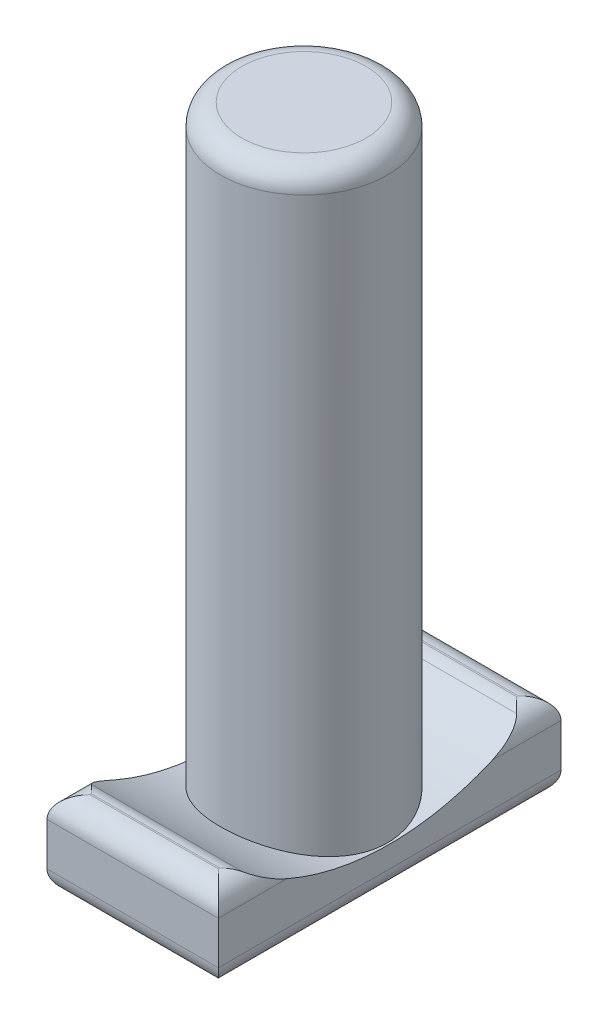
SolidWorks part; units mm, degrees
ref_plane "前视基准面" through (0, 0, 0) normal (0, 0, 1) x (1, 0, 0)
ref_plane "上视基准面" through (0, 0, 0) normal (0, 1, 0) x (1, 0, 0)
ref_plane "右视基准面" through (0, 0, 0) normal (1, 0, 0) x (0, 0, -1)
sketch "草图1" plane through (0, 0, 0) normal (0, 1, 0) x (1, 0, 0)
  line L1 (0, 0) -> (4, 0)
  line L2 (0, 0) -> (0, 8)
  line L3 (0, 8) -> (4, 8)
  line L4 (4, 0) -> (4, 8)
  circle A0 centre (2, 4) radius 1.95
  point P9 (4, 4.9563)
  dimension "D3" = 3.9
  dimension "D4" = 4
  dimension "D1" = 4
  dimension "D2" = 8
  dimension "D5" = 2
extrude "凸台-拉伸1" add sketch "草图1" along normal blind 2
sketch "草图2" plane through (0, 0, 0) normal (0, -1, 0) x (1, 0, 0)
  circle A0 centre (2, -4) radius 1.95
sketch "草图3" plane through (0, 0, 0) normal (-1, 0, 0) x (0, 0, 1)
  line L0 (-8, 2) -> (0, 2) construction
  line L1 (-8, 2) -> (-8, 0) construction
  circle A0 centre (-4, 7) radius 6
  dimension "D2" = 12
  dimension "D1" = 5
  dimension "D3" = 4
extrude "切除-拉伸1" cut sketch "草图3" against normal through all
extrude "凸台-拉伸3" add sketch "草图2" against normal blind 15
fillet "圆角3" radius 0.5 13 edges at (2, 0, 0) (4, 0, -4) (2, 0, -8) (0, 0, -4) (2, 15, -5.95) (2, 2, 0) (0, 2, -0.3417) (2, 2, -7.3166) (2, 2, -0.6834) (4, 2, -0.3417) (2, 2, -8) (4, 2, -7.6583) (0, 2, -7.6583)
